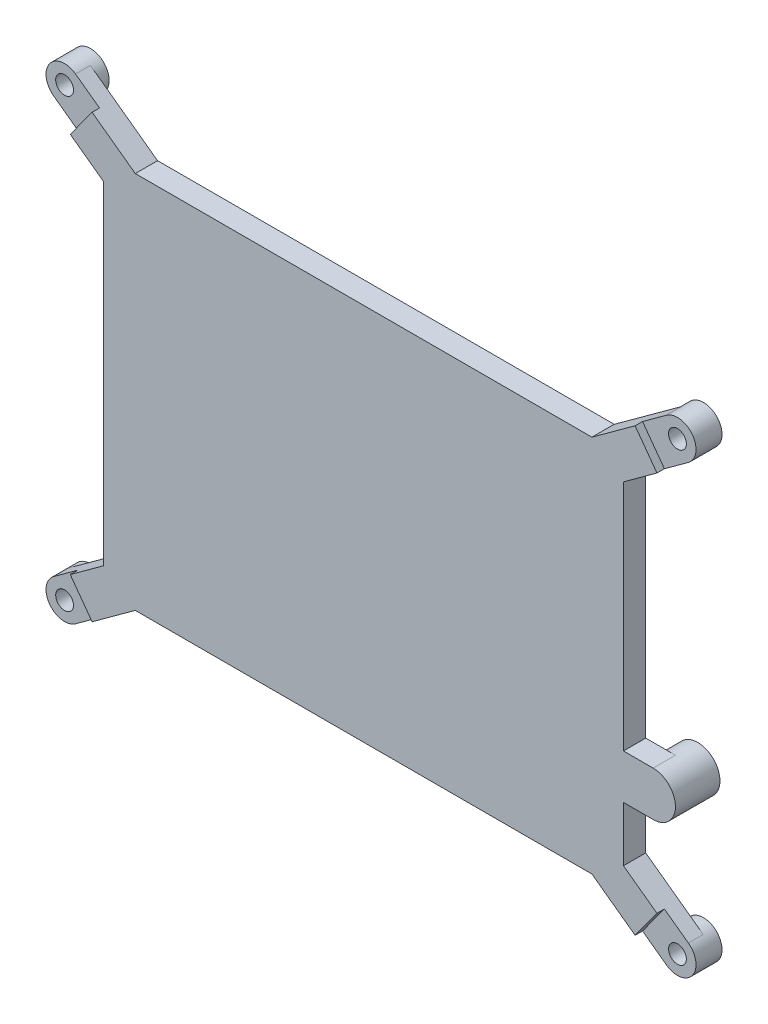
SolidWorks part; units mm, degrees
ref_plane "Front Plane" through (0, 0, 0) normal (0, 0, 1) x (1, 0, 0)
ref_plane "Top Plane" through (0, 0, 0) normal (0, 1, 0) x (1, 0, 0)
ref_plane "Right Plane" through (0, 0, 0) normal (1, 0, 0) x (0, 0, -1)
sketch "Sketch1" plane through (0, 0, 0) normal (0, 0, 1) x (1, 0, 0)
  line L0 (-41.275, 57.6) -> (-41.275, -2.5) construction
  line L1 (-41.275, 57.6) -> (41.275, 57.6) construction
  line L2 (41.275, 57.6) -> (41.275, -2.5) construction
  line L3 (41.275, -2.5) -> (-41.275, -2.5) construction
  line L4 (-39.8036, 59.6211) -> (-30.7525, 53.0315)
  line L5 (-42.7464, 55.5789) -> (-35, 49.9391)
  line L6 (-39.8036, -4.5211) -> (-30.7525, 2.0685)
  line L7 (-42.7464, -0.4789) -> (-35, 5.1609)
  line L8 (-41.275, -2.5) -> (41.275, 57.6) construction
  line L9 (-41.275, 57.6) -> (41.275, -2.5) construction
  line L10 (-35, 49.9391) -> (-35, 53.0315) construction
  line L11 (-30.7525, 2.0685) -> (30.7525, 2.0685)
  line L12 (39, 12.55) -> (35, 12.55)
  line L13 (-30.7525, 53.0315) -> (30.7525, 53.0315)
  line L14 (35, 5.1609) -> (35, 12.55)
  line L15 (-35, 2.0685) -> (35, 53.0315) construction
  line L16 (-35, 53.0315) -> (35, 2.0685) construction
  line L17 (35, 5.1609) -> (42.7464, -0.4789)
  line L18 (30.7525, 2.0685) -> (39.8036, -4.5211)
  line L19 (30.7525, 53.0315) -> (39.8036, 59.6211)
  line L20 (35, 49.9391) -> (42.7464, 55.5789)
  line L21 (-35, 53.0315) -> (-30.7525, 53.0315) construction
  line L22 (30.7525, 53.0315) -> (35, 53.0315) construction
  line L23 (35, 53.0315) -> (35, 49.9391) construction
  line L24 (35, 5.1609) -> (35, 2.0685) construction
  line L25 (35, 2.0685) -> (30.7525, 2.0685) construction
  line L26 (-35, 5.1609) -> (-35, 2.0685) construction
  line L27 (-35, 2.0685) -> (-30.7525, 2.0685) construction
  line L29 (37, 15.55) -> (-31, 15.55) construction
  line L30 (39, 18.55) -> (35, 18.55)
  line L33 (-35, 5.1609) -> (-35, 49.9391)
  line L36 (35, 18.55) -> (35, 49.9391)
  arc A0 (-39.8036, 59.6211) -> (-42.7464, 55.5789) centre (-41.275, 57.6) ccw
  arc A1 (-42.7464, -0.4789) -> (-39.8036, -4.5211) centre (-41.275, -2.5) ccw
  arc A2 (42.7464, 55.5789) -> (39.8036, 59.6211) centre (41.275, 57.6) ccw
  arc A3 (39.8036, -4.5211) -> (42.7464, -0.4789) centre (41.275, -2.5) ccw
  arc A4 (39, 12.55) -> (39, 18.55) centre (39, 15.55) ccw
  point P16 (0, 27.55)
  dimension "D1" = 5
  dimension "D5" = 4
  dimension "D8" = 3
  dimension "D2" = 60.1
  dimension "D3" = 82.55
  dimension "D4" = 70
  dimension "D7" = 12
extrude "Boss-Extrude1" add sketch "Sketch1" along normal blind 3
sketch "Sketch5" plane through (0, 0, 0) normal (0, 0, -1) x (-1, 0, 0)
  circle A0 centre (-41.275, 57.6) radius 2.5
  circle A1 centre (41.275, 57.6) radius 2.5
  circle A2 centre (-41.275, -2.5) radius 2.5
  circle A3 centre (41.275, -2.5) radius 2.5
  arc A4 (42.7464, 55.5789) -> (39.8036, 59.6211) centre (41.275, 57.6) ccw construction
extrude "Boss-Extrude4" add sketch "Sketch5" along normal blind 1.5
sketch "Sketch3" plane through (0, 0, 3) normal (0, 0, 1) x (1, 0, 0)
  circle A0 centre (-41.275, 57.6) radius 1.2
  circle A1 centre (41.275, 57.6) radius 1.2
  circle A2 centre (-41.275, -2.5) radius 1.2
  circle A3 centre (41.275, -2.5) radius 1.2
  dimension "D1" = 2.4
extrude "Cut-Extrude1" cut sketch "Sketch3" against normal through all
sketch "Sketch7" plane through (0, 0, 3) normal (0, 0, 1) x (1, 0, 0)
  line L0 (-36.5698, 57.2668) -> (-39.5127, 53.2246)
  line L1 (-30.7525, 53.0315) -> (-39.8036, 59.6211) construction
  line L2 (-42.7464, 55.5789) -> (-35, 49.9391) construction
  line L3 (-39.5127, 53.2246) -> (-42.7464, 55.5789)
  line L4 (-36.5698, 57.2668) -> (-39.8036, 59.6211)
  line L5 (-42.7464, -0.4789) -> (-39.5127, 1.8754)
  line L6 (-35, 5.1609) -> (-42.7464, -0.4789) construction
  line L7 (-39.5127, 1.8754) -> (-36.5698, -2.1668)
  line L8 (-39.8036, -4.5211) -> (-30.7525, 2.0685) construction
  line L9 (-36.5698, -2.1668) -> (-39.8036, -4.5211)
  line L10 (39.8036, -4.5211) -> (36.5698, -2.1668)
  line L11 (30.7525, 2.0685) -> (39.8036, -4.5211) construction
  line L12 (36.5698, -2.1668) -> (39.5127, 1.8754)
  line L13 (42.7464, -0.4789) -> (35, 5.1609) construction
  line L14 (39.5127, 1.8754) -> (42.7464, -0.4789)
  line L15 (39.8036, 59.6211) -> (36.5698, 57.2668)
  line L16 (39.8036, 59.6211) -> (30.7525, 53.0315) construction
  line L17 (36.5698, 57.2668) -> (39.5127, 53.2246)
  line L18 (35, 49.9391) -> (42.7464, 55.5789) construction
  line L19 (39.5127, 53.2246) -> (42.7464, 55.5789)
  arc A0 (-39.8036, 59.6211) -> (-42.7464, 55.5789) centre (-41.275, 57.6) ccw
  arc A1 (-42.7464, -0.4789) -> (-39.8036, -4.5211) centre (-41.275, -2.5) ccw construction
  arc A2 (-42.7464, -0.4789) -> (-39.8036, -4.5211) centre (-41.275, -2.5) ccw
  arc A3 (39.8036, -4.5211) -> (42.7464, -0.4789) centre (41.275, -2.5) ccw
  arc A4 (42.7464, 55.5789) -> (39.8036, 59.6211) centre (41.275, 57.6) ccw
  dimension "D1" = 4
extrude "Cut-Extrude2" cut sketch "Sketch7" against normal blind 1
sketch "Sketch8" plane through (0, 0, 0) normal (0, 0, -1) x (-1, 0, 0)
  circle A0 centre (-39, 15.55) radius 3
  circle A1 centre (30, 8.55) radius 3
  arc A2 (-39, 18.55) -> (-39, 12.55) centre (-39, 15.55) ccw construction
  dimension "D1" = 69
  dimension "D2" = 7
extrude "Boss-Extrude6" add sketch "Sketch8" along normal blind 3
hole_wizard "CSK for M2 Flat Head Machine Screw1" positions "Sketch10" profile "Sketch11" countersink size "M2" standard "ANSI Metric"
sketch "Sketch10" plane through (0, 0, -3) normal (0, 0, -1) x (-1, 0, 0)
  point P0 (-39, 15.55)
  point P3 (30, 8.55)
sketch "Sketch11" plane through (39, 15.55, -3) normal (1, 0, 0) x (0, 1, 0)
  line L0 (0, 0) -> (0, 4.9013)
  line L1 (0, 4.9013) -> (1.5, 4)
  line L2 (1.5, 4) -> (1.5, 0.5038)
  line L3 (1.5, 0.5038) -> (1.635, 0)
  line L5 (1.635, 0) -> (0, 0)
  line L6 (-1.5, 0.5038) -> (-1.635, 0) construction
  line L10 (0, 4.9013) -> (-1.5, 4) construction
  line L11 (0, -6.35) -> (0, 107.95) construction
  dimension "Hole Dia." = 3
  dimension "Hole Depth" = 4
  dimension "Near C'Sink Dia." = 3.27
  dimension "Near C'Sink Angle" = 30
  dimension "Drill Angle" = 118
